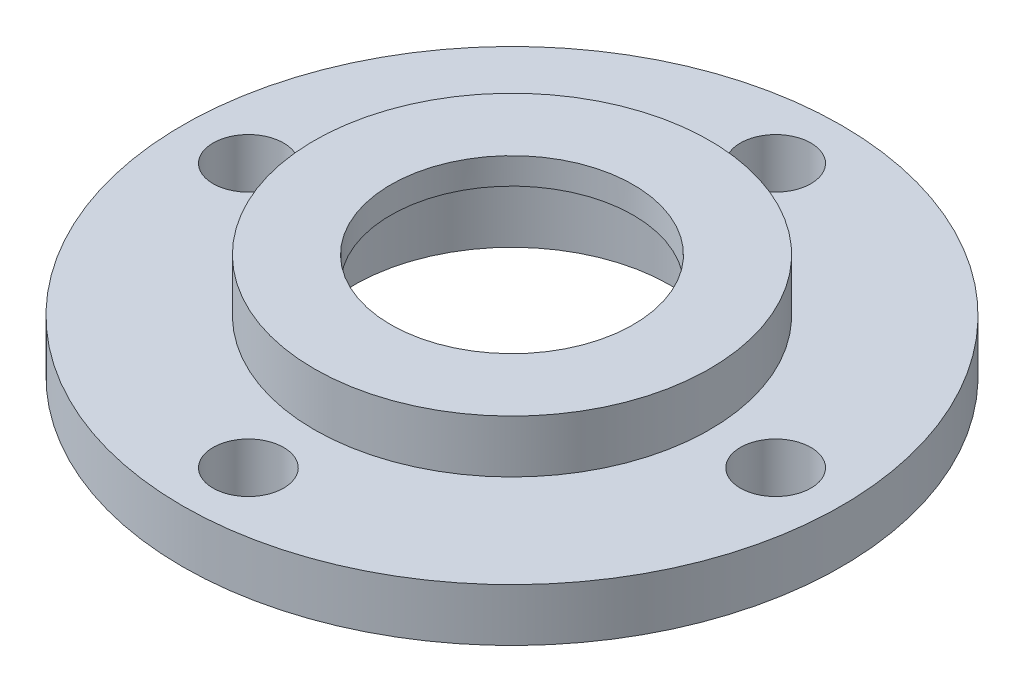
SolidWorks part; units mm, degrees
ref_plane "Front Plane" through (0, 0, 0) normal (0, 0, 1) x (1, 0, 0)
ref_plane "Top Plane" through (0, 0, 0) normal (0, 1, 0) x (1, 0, 0)
ref_plane "Right Plane" through (0, 0, 0) normal (1, 0, 0) x (0, 0, -1)
sketch "Sketch1" plane through (0, 0, 0) normal (0, 1, 0) x (1, 0, 0)
  circle A0 centre (0, 0) radius 15.875
  dimension "D1" = 31.75
extrude "Boss-Extrude1" add sketch "Sketch1" along normal blind 2.54
sketch "Sketch2" plane through (0, 2.54, 0) normal (0, 1, 0) x (1, 0, 0)
  circle A0 centre (0, 0) radius 9.525
  dimension "D1" = 19.05
extrude "Boss-Extrude2" add sketch "Sketch2" along normal blind 2.54
sketch "Sketch3" plane through (0, 0, 0) normal (0, -1, 0) x (1, 0, 0)
  circle A0 centre (0, 0) radius 7.62
  dimension "D1" = 15.24
extrude "Cut-Extrude1" cut sketch "Sketch3" against normal blind 3.81
sketch "Sketch4" plane through (0, 5.08, 0) normal (0, 1, 0) x (1, 0, 0)
  circle A0 centre (0, 0) radius 5.842
  dimension "D1" = 11.684
extrude "Cut-Extrude2" cut sketch "Sketch4" against normal up to next
sketch "Sketch5" plane through (0, 2.54, 0) normal (0, 1, 0) x (1, 0, 0)
  line L0 (0, 15.875) -> (0, 0) construction
  circle A0 centre (0, 12.7) radius 1.7
  circle A1 centre (0, 0) radius 15.875 construction
  circle A2 centre (12.7, 0) radius 1.7
  circle A3 centre (0, -12.7) radius 1.7
  circle A4 centre (-12.7, 0) radius 1.7
  point P18 (0, 0)
  dimension "D2" = 3.4
  dimension "D1" = 12.7
  dimension "D3" = 4
extrude "Cut-Extrude3" cut sketch "Sketch5" against normal up to next
